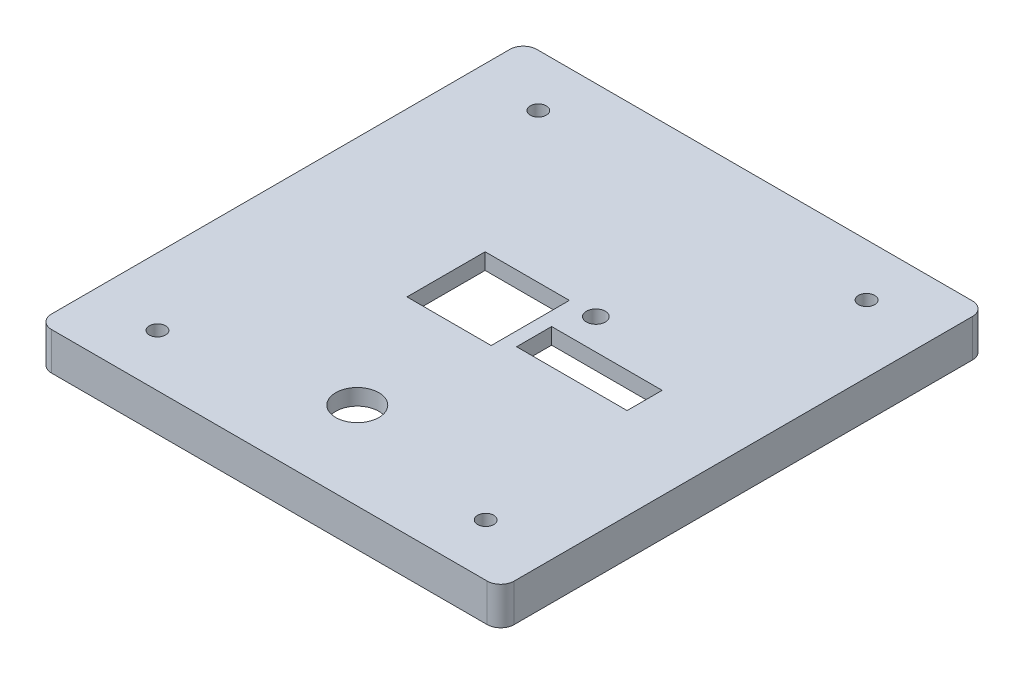
SolidWorks part; units mm, degrees
ref_plane "前视基准面" through (0, 0, 0) normal (0, 0, 1) x (1, 0, 0)
ref_plane "上视基准面" through (0, 0, 0) normal (0, 1, 0) x (1, 0, 0)
ref_plane "右视基准面" through (0, 0, 0) normal (1, 0, 0) x (0, 0, -1)
sketch "草图1" plane through (0, 0, 0) normal (0, 1, 0) x (1, 0, 0)
  line L0 (38.265, 85.1381) -> (38.265, -4.8619) construction
  line L1 (-4.635, 85.1381) -> (81.165, 85.1381)
  line L2 (-4.635, 85.1381) -> (-4.635, -4.8619)
  line L3 (-4.635, -4.8619) -> (81.165, -4.8619)
  line L4 (81.165, 85.1381) -> (81.165, -4.8619)
  line L5 (81.165, 40.1381) -> (-9.9096, 40.1381) construction
  line L6 (5.626, 77.8571) -> (70.904, 77.8571)
  line L11 (5.626, 77.8571) -> (5.626, 2.4191)
  line L12 (5.626, 2.4191) -> (70.904, 2.4191)
  line L13 (70.904, 77.8571) -> (70.904, 2.4191)
  point P10 (38.265, 85.1381)
  point P12 (38.265, 40.1381)
  point P13 (-7.2723, 40.1381)
extrude "凸台-拉伸1" add sketch "草图1" along normal blind 4
sketch "草图6" plane through (0, 4, 0) normal (0, 1, 0) x (1, 0, 0)
  line L1 (-4.635, 85.1381) -> (81.165, 85.1381)
  line L2 (-4.635, 85.1381) -> (-4.635, -4.8619)
  line L3 (-4.635, -4.8619) -> (81.165, -4.8619)
  line L4 (81.165, 85.1381) -> (81.165, -4.8619)
extrude "凸台-拉伸2" add sketch "草图6" along normal blind 3
sketch "草图7" plane through (0, 0, 0) normal (0, -1, 0) x (1, 0, 0)
  line L1 (69.697, -85.1381) -> (54.297, -85.1381)
  line L3 (81.165, -85.1381) -> (-4.635, -85.1381) construction
  line L4 (69.697, -85.1381) -> (69.697, -77.8571)
  line L5 (70.904, -77.8571) -> (5.626, -77.8571) construction
  line L6 (54.297, -85.1381) -> (54.297, -77.8571)
  line L7 (54.297, -77.8571) -> (69.697, -77.8571)
  dimension "D1" = 11.468
extrude "切除-拉伸1" cut sketch "草图7" against normal blind 3
fillet "圆角1" radius 2.5 4 edges at (81.165, 3.5, -85.1381) (81.165, 3.5, 4.8619) (-4.635, 3.5, 4.8619) (-4.635, 3.5, -85.1381)
sketch "草图9" plane through (0, 7, 0) normal (0, 1, 0) x (1, 0, 0)
  line L0 (64.255, 41.9981) -> (47.2992, 41.9981)
  line L1 (-2.135, -4.8619) -> (78.665, -4.8619) construction
  line L2 (64.255, 41.9981) -> (64.255, 35.4981)
  line L3 (64.255, 35.4981) -> (43.755, 35.4981)
  line L4 (43.755, 35.4981) -> (43.755, 41.9981)
  line L5 (43.755, 41.9981) -> (47.2992, 41.9981)
  line L6 (81.165, -2.3619) -> (81.165, 82.6381) construction
  dimension "D1" = 40.36
  dimension "D2" = 16.91
extrude "切除-拉伸2" cut sketch "草图9" against normal through all
sketch "草图10" plane through (0, 7, 0) normal (0, 1, 0) x (1, 0, 0)
  line L0 (-2.135, -4.8619) -> (78.665, -4.8619) construction
  line L1 (81.165, -2.3619) -> (81.165, 82.6381) construction
  circle A2 centre (46.265, 47.6881) radius 1.75
  dimension "D1" = 52.55
  dimension "D3" = 3.5
  dimension "D2" = 34.9
extrude "切除-拉伸3" cut sketch "草图10" against normal through all
sketch "草图11" plane through (0, 7, 0) normal (0, 1, 0) x (1, 0, 0)
  line L0 (41.205, 47.8381) -> (41.205, 33.3381)
  line L1 (41.205, 33.3381) -> (25.584, 33.3381)
  line L2 (25.584, 33.3381) -> (25.584, 47.8381)
  line L3 (25.584, 47.8381) -> (41.205, 47.8381)
  line L4 (81.165, -2.3619) -> (81.165, 82.6381) construction
  line L5 (-2.135, -4.8619) -> (78.665, -4.8619) construction
  point P6 (0, 0)
  point P8 (47.8598, -4.8619)
  dimension "D1" = 39.96
  dimension "D2" = 38.2
  dimension "D3" = 14.5
extrude "切除-拉伸4" cut sketch "草图11" against normal through all
sketch "草图12" plane through (0, 7, 0) normal (0, 1, 0) x (1, 0, 0)
  line L5 (38.265, 85.1381) -> (38.265, -4.8619) construction
  line L6 (78.665, 85.1381) -> (-2.135, 85.1381) construction
  line L7 (5.626, 77.8571) -> (5.626, 2.4191) construction
  line L8 (70.904, 77.8571) -> (5.626, 77.8571) construction
  line L9 (38.265, 40.1381) -> (-3.1279, 40.1381) construction
  line L10 (-2.135, -4.8619) -> (78.665, -4.8619) construction
  line L11 (-3.1279, 40.1381) -> (72.5408, 40.1381) construction
  line L12 (70.904, 2.4191) -> (70.904, 77.8571) construction
  circle A0 centre (7.826, 75.4571) radius 1.5
  circle A5 centre (68.704, 75.4571) radius 1.5
  circle A6 centre (7.826, 4.8191) radius 1.5
  circle A7 centre (68.704, 4.8191) radius 1.5
  point P21 (71.1271, 76.0301)
  dimension "D1" = 2.2
  dimension "D5" = 3
  dimension "D2" = 2.4
  dimension "D3" = 2.4
  dimension "D4" = 2.2
sketch "草图15" plane through (0, 7, 0) normal (0, 1, 0) x (1, 0, 0)
  circle A0 centre (38.3539, 11.3566) radius 4
extrude "切除-拉伸8" cut sketch "草图15" against normal through all
extrude "切除-拉伸15" cut sketch "草图12" against normal blind 10 contours A0 | A6 | A7 | A5
